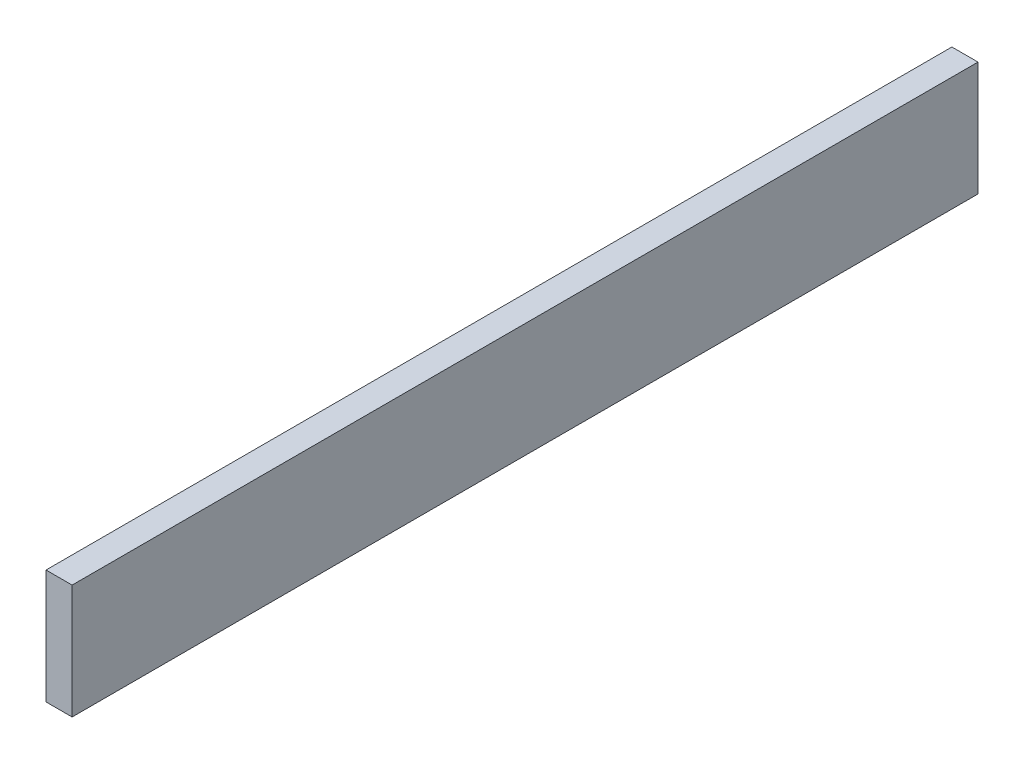
SolidWorks part; units mm, degrees
ref_plane "Front Plane" through (0, 0, 0) normal (0, 0, 1) x (1, 0, 0)
ref_plane "Top Plane" through (0, 0, 0) normal (0, 1, 0) x (1, 0, 0)
ref_plane "Right Plane" through (0, 0, 0) normal (1, 0, 0) x (0, 0, -1)
sketch "Sketch1" plane through (0, 0, 0) normal (1, 0, 0) x (0, 0, -1)
  line L1 (0, 0) -> (555, 0)
  line L2 (0, 0) -> (0, 70)
  line L3 (0, 70) -> (555, 70)
  line L4 (555, 0) -> (555, 70)
  dimension "D1" = 555
  dimension "D2" = 70
extrude "Boss-Extrude1" add sketch "Sketch1" along normal blind 16
